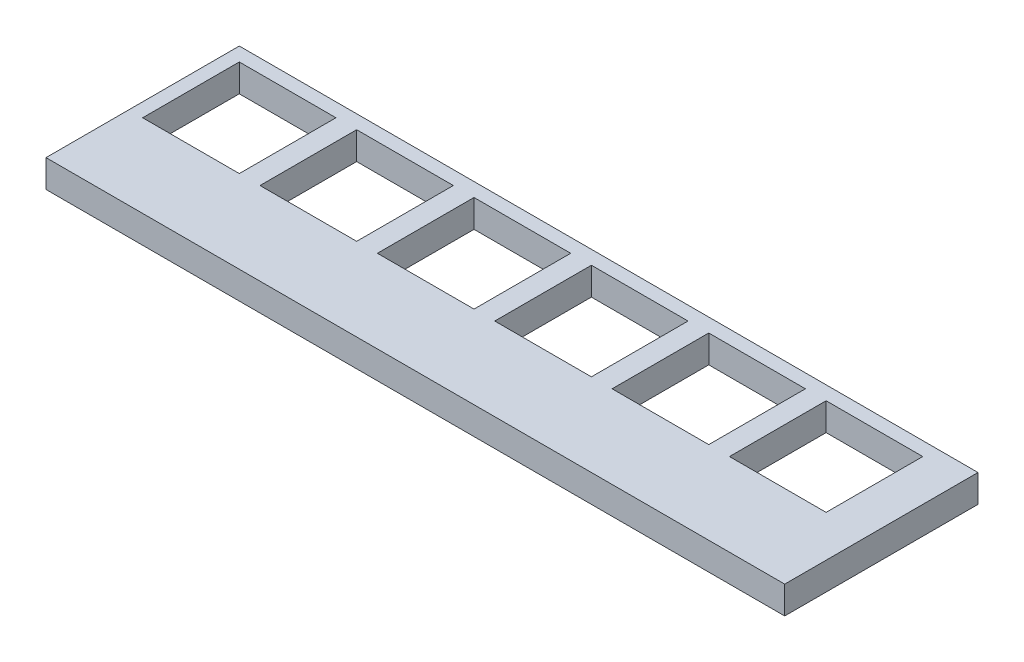
SolidWorks part; units mm, degrees
material "Сосна"
ref_plane "Спереди" through (0, 0, 0) normal (0, 0, 1) x (1, 0, 0)
ref_plane "Сверху" through (0, 0, 0) normal (0, 1, 0) x (1, 0, 0)
ref_plane "Справа" through (0, 0, 0) normal (1, 0, 0) x (0, 0, -1)
sketch3d "Трехмерный эскиз1"
  line L10 (26.5614, 0, 21.9842) -> (26.5614, 0, 49.9842)
  line L11 (-80.4386, 0, 21.9842) -> (26.5614, 0, 21.9842)
  line L16 (20.5614, 0, 37.9842) -> (20.5614, 0, 23.9842)
  line L17 (6.5614, 0, 23.9842) -> (20.5614, 0, 23.9842)
  line L22 (6.5614, 0, 37.9842) -> (6.5614, 0, 23.9842)
  line L23 (6.5614, 0, 37.9842) -> (20.5614, 0, 37.9842)
  line L28 (-80.4386, 0, 49.9842) -> (26.5614, 0, 49.9842)
  line L29 (-80.4386, 0, 21.9842) -> (-80.4386, 0, 49.9842)
  line L34 (-78.4386, 0, 37.9842) -> (-78.4386, 0, 23.9842)
  line L35 (-78.4386, 0, 23.9842) -> (-64.4386, 0, 23.9842)
  line L41 (-64.4386, 0, 37.9842) -> (-64.4386, 0, 23.9842)
  line L42 (-78.4386, 0, 37.9842) -> (-64.4386, 0, 37.9842)
  line L46 (-61.4386, 0, 37.9842) -> (-61.4386, 0, 23.9842)
  line L47 (-61.4386, 0, 23.9842) -> (-47.4386, 0, 23.9842)
  line L52 (-47.4386, 0, 37.9842) -> (-47.4386, 0, 23.9842)
  line L53 (-61.4386, 0, 37.9842) -> (-47.4386, 0, 37.9842)
  line L58 (-44.4386, 0, 23.9842) -> (-30.4386, 0, 23.9842)
  line L59 (-30.4386, 0, 37.9842) -> (-30.4386, 0, 23.9842)
  line L64 (-44.4386, 0, 37.9842) -> (-44.4386, 0, 23.9842)
  line L65 (-44.4386, 0, 37.9842) -> (-30.4386, 0, 37.9842)
  line L70 (-27.4386, 0, 23.9842) -> (-27.4386, 0, 37.9842)
  line L71 (-27.4386, 0, 23.9842) -> (-13.4386, 0, 23.9842)
  line L93 (-13.4386, 0, 23.9842) -> (-13.4386, 0, 37.9842)
  line L94 (-27.4386, 0, 37.9842) -> (-13.4386, 0, 37.9842)
  line L167 (-10.4386, 0, 37.9842) -> (3.5614, 0, 37.9842)
  line L168 (-10.4386, 0, 23.9842) -> (-10.4386, 0, 37.9842)
  line L169 (3.5614, 0, 23.9842) -> (3.5614, 0, 37.9842)
  line L170 (-10.4386, 0, 23.9842) -> (3.5614, 0, 23.9842)
  point P114 (-94.0669, -1.1459, -18.7948)
  point P263 (-94.6676, 0, -16.0083)
  point P264 (-94.6676, 0, -16.0083)
  point P265 (-94.6676, 0, -16.0083)
  point P267 (-91.2804, 0, 28.0254)
  dimension "D1" = 14
  dimension "D3" = 14
  dimension "D2" = 14
  dimension "D6" = 107
  dimension "D4" = 2
  dimension "D5" = 28
  dimension "D7" = 2
  dimension "D11" = 3
  dimension "D8" = 3
  dimension "D9" = 3
  dimension "D10" = 3
  dimension "D12" = 3
extrude "Бобышка-Вытянуть1" add sketch "Трехмерный эскиз1" along direction (0, 1, 0) on the side of the normal blind 4
